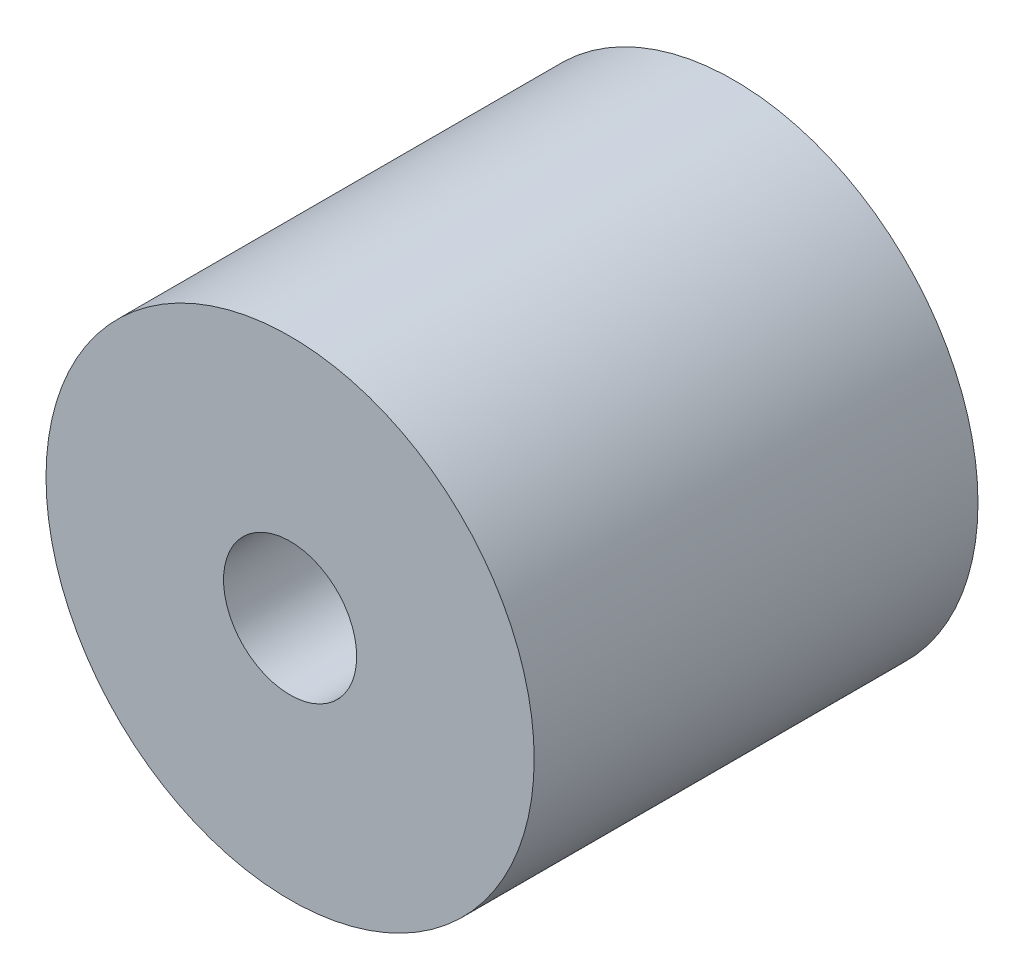
SolidWorks part; units mm, degrees
ref_plane "Front Plane" through (0, 0, 0) normal (0, 0, 1) x (1, 0, 0)
ref_plane "Top Plane" through (0, 0, 0) normal (0, 1, 0) x (1, 0, 0)
ref_plane "Right Plane" through (0, 0, 0) normal (1, 0, 0) x (0, 0, -1)
sketch "Sketch1" plane through (0, 0, 0) normal (0, 0, 1) x (1, 0, 0)
  circle A0 centre (0, 0) radius 5.5
  circle A1 centre (0, 0) radius 1.5
extrude "Boss-Extrude1" add sketch "Sketch1" along normal blind 10
